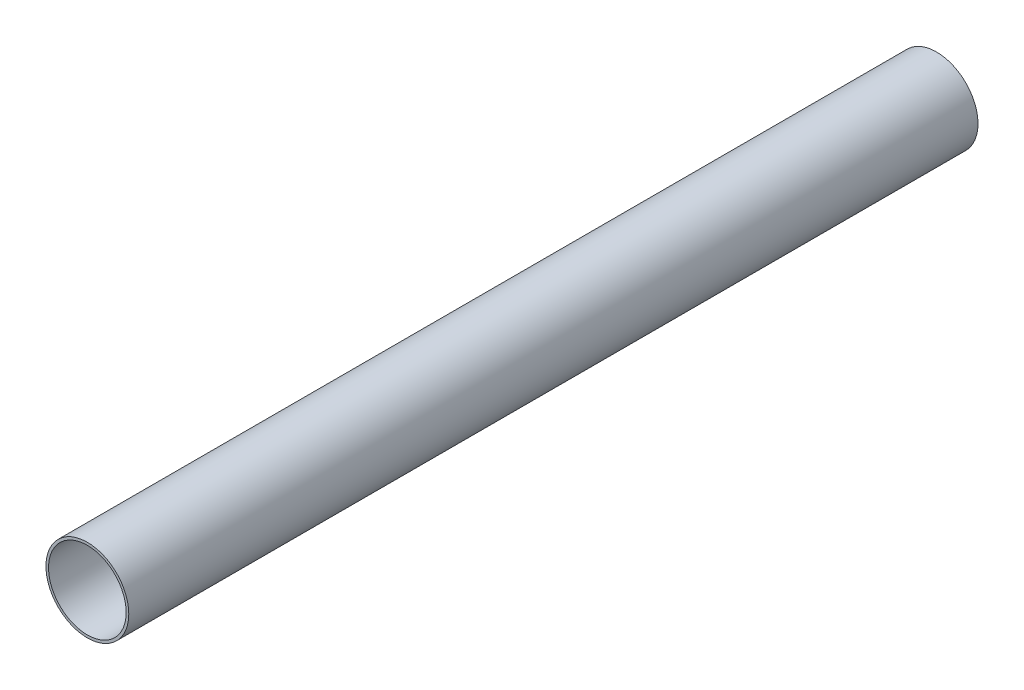
SolidWorks part; units mm, degrees
ref_plane "Front Plane" through (0, 0, 0) normal (0, 0, 1) x (1, 0, 0)
ref_plane "Top Plane" through (0, 0, 0) normal (0, 1, 0) x (1, 0, 0)
ref_plane "Right Plane" through (0, 0, 0) normal (1, 0, 0) x (0, 0, -1)
sketch "Sketch1" plane through (0, 0, 0) normal (0, 0, 1) x (1, 0, 0)
  circle A0 centre (0, 0) radius 50.8
  circle A1 centre (0, 0) radius 47.625
  dimension "D1" = 101.6
  dimension "D2" = 95.25
extrude "Boss-Extrude1" add sketch "Sketch1" along normal blind 1041.4
